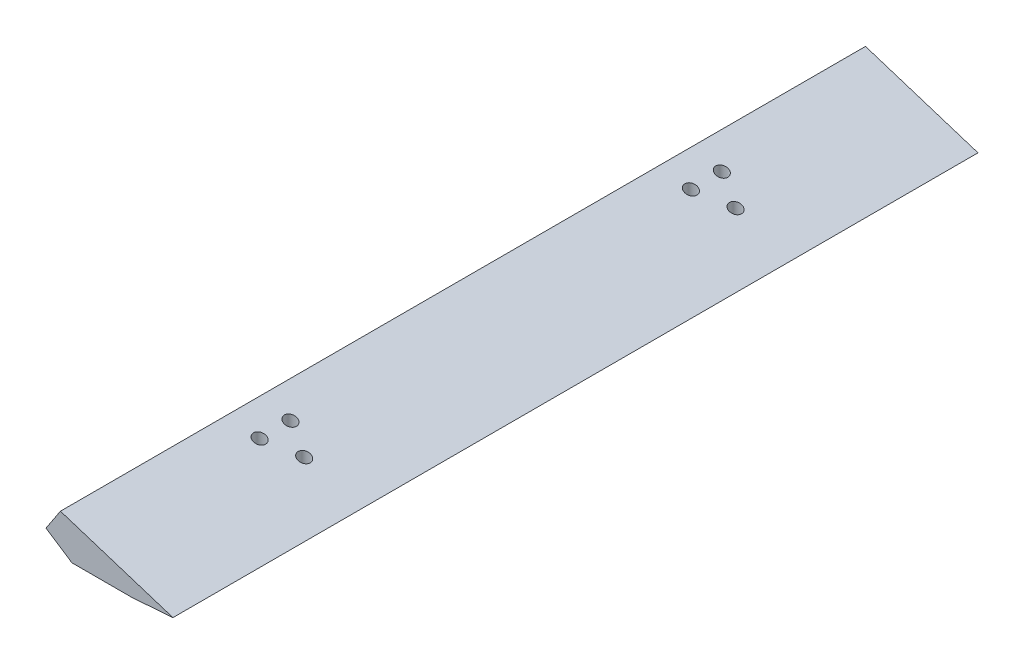
SolidWorks part; units mm, degrees
ref_plane "前视基准面" through (0, 0, 0) normal (0, 0, 1) x (1, 0, 0)
ref_plane "上视基准面" through (0, 0, 0) normal (0, 1, 0) x (1, 0, 0)
ref_plane "右视基准面" through (0, 0, 0) normal (1, 0, 0) x (0, 0, -1)
other "Configuration Table"
sketch "草图1" plane through (0, 0, 0) normal (0, 0, 1) x (1, 0, 0)
  line L0 (-7.5, 0) -> (7.5, 0)
  line L1 (-7.5, 0) -> (-13.931, 4.2468)
  line L2 (-13.931, 4.2468) -> (-10.343, 9.6801)
  line L4 (-10.343, 9.6801) -> (17.6078, 0.7557)
  line L8 (17.6078, 0.7557) -> (7.5, 0)
  point P4 (0, 0)
  dimension "D1" = 15
extrude "凸台-拉伸1" add sketch "草图1" along normal mid plane 200
sketch "草图2" plane through (0, 0, 0) normal (0, -1, 0) x (1, 0, 0)
  circle A1 centre (3.794, 53.579) radius 1.5
  circle A4 centre (3.794, -53.579) radius 1.5
  circle A6 centre (-3.4528, 57.4153) radius 1.5
  circle A7 centre (-3.4528, 49.7426) radius 1.5
  circle A8 centre (-3.4528, -49.7426) radius 1.5
  circle A9 centre (-3.4528, -57.4153) radius 1.5
extrude "切除-拉伸1" cut sketch "草图2" against normal through all
